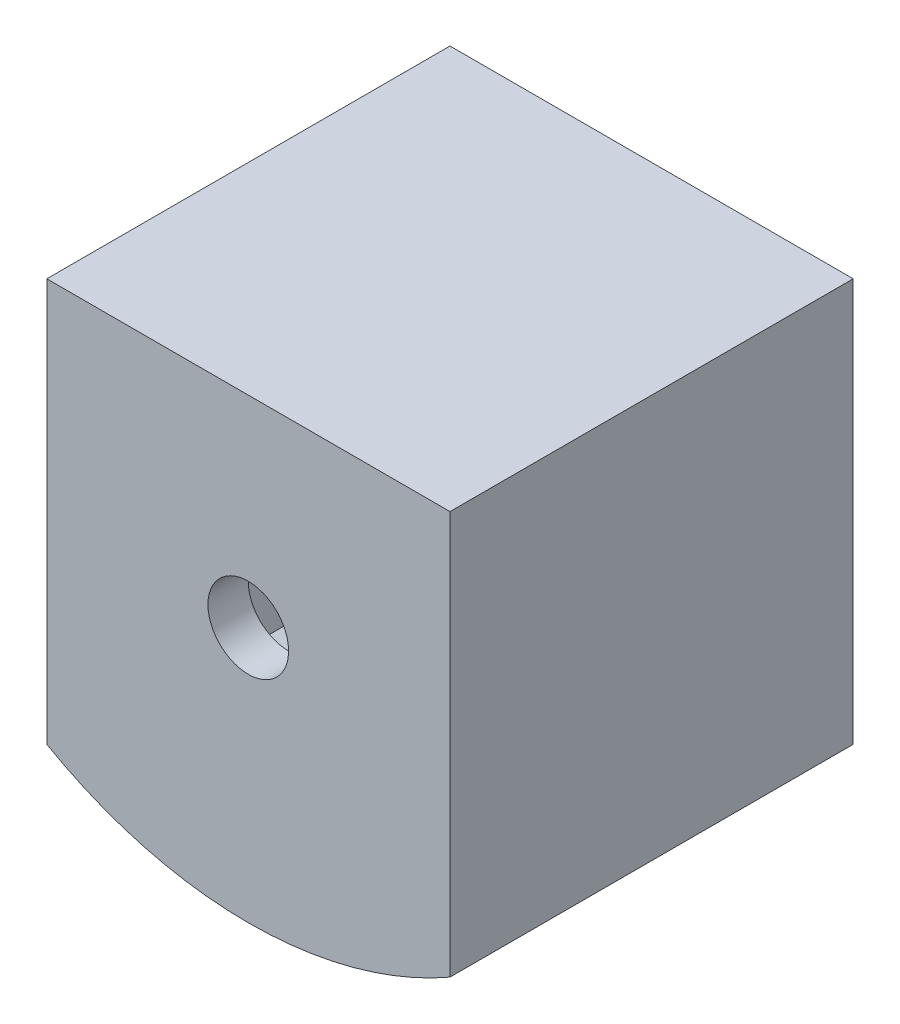
SolidWorks part; units mm, degrees
ref_plane "Front Plane" through (0, 0, 0) normal (0, 0, 1) x (1, 0, 0)
ref_plane "Top Plane" through (0, 0, 0) normal (0, 1, 0) x (1, 0, 0)
ref_plane "Right Plane" through (0, 0, 0) normal (1, 0, 0) x (0, 0, -1)
sketch "Sketch1" plane through (0, 0, 0) normal (0, 0, 1) x (1, 0, 0)
  line L2 (15, -15) -> (15, 15)
  line L3 (15, 15) -> (-15, 15)
  line L4 (-15, -15) -> (-15, 15)
  line L5 (15, -15) -> (-15, 15) construction
  line L6 (15, 15) -> (-15, -15) construction
  arc A3 (-15, -15) -> (15, -15) centre (0, 11.0898) ccw
  point P0 (0, 0)
extrude "Boss-Extrude1" add sketch "Sketch1" along normal blind 30
shell "Shell13" thickness 3
sketch "Sketch3" plane through (0, 0, 27) normal (0, 0, -1) x (-1, 0, 0)
  circle A0 centre (0.0103, 0.0076) radius 3
  point P2 (0.0103, 0.0076)
  point P3 (0, 0)
extrude "Cut-Extrude2" cut sketch "Sketch3" against normal blind 3
sketch "Sketch4" plane through (0, 0, 0) normal (0, 0, -1) x (-1, 0, 0)
  line L0 (12, 12) -> (12, -13.2024) construction
  line L1 (-5, 14) -> (5, 14)
  line L2 (-5, 14) -> (-5, 13)
  line L3 (-5, 13) -> (5, 13)
  line L4 (5, 14) -> (5, 13)
  line L5 (-14, 5) -> (-13, 5)
  line L6 (-14, 5) -> (-14, -5)
  line L7 (-14, -5) -> (-13, -5)
  line L8 (-13, 5) -> (-13, -5)
  line L9 (-3.5, -17) -> (3.5, -17)
  line L10 (-3.5, -17) -> (-3.5, -18)
  line L11 (-3.5, -18) -> (3.5, -18)
  line L12 (3.5, -17) -> (3.5, -18)
  line L13 (13, 5) -> (14, 5)
  line L14 (13, 5) -> (13, -5)
  line L15 (13, -5) -> (14, -5)
  line L16 (14, 5) -> (14, -5)
  line L17 (-12, -13.2024) -> (-12, 12) construction
  line L18 (-12, 12) -> (12, 12) construction
  point P16 (0, -17)
  point P18 (-13, 0)
  point P19 (13, 0)
  point P20 (0, 13)
  dimension "D1" = 1
  dimension "D2" = 1
  dimension "D3" = 1
  dimension "D4" = 17
extrude "Cut-Extrude3" cut sketch "Sketch4" against normal blind 5
